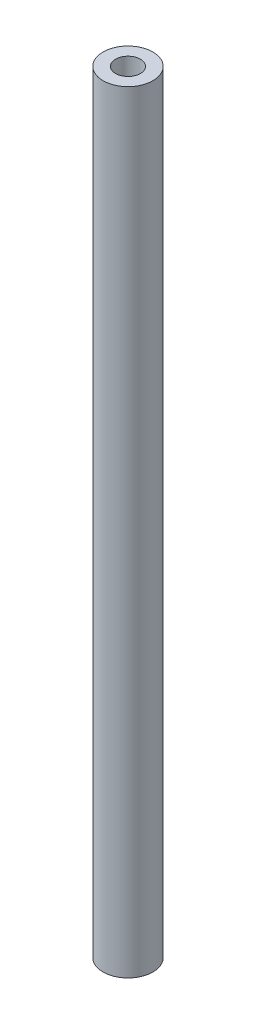
SolidWorks part; units mm, degrees
material "PTFE (general)"
ref_plane "Front" through (0, 0, 0) normal (0, 0, 1) x (1, 0, 0)
ref_plane "Top" through (0, 0, 0) normal (0, 1, 0) x (1, 0, 0)
ref_plane "Right" through (0, 0, 0) normal (1, 0, 0) x (0, 0, -1)
sketch "Sketch1" plane through (0, 0, 0) normal (0, 1, 0) x (1, 0, 0)
  circle A0 centre (0, 0) radius 2
  circle A1 centre (0, 0) radius 1
  dimension "D1" = 2
  dimension "D2" = 4
extrude "Boss-Extrude1" add sketch "Sketch1" along normal blind 62
